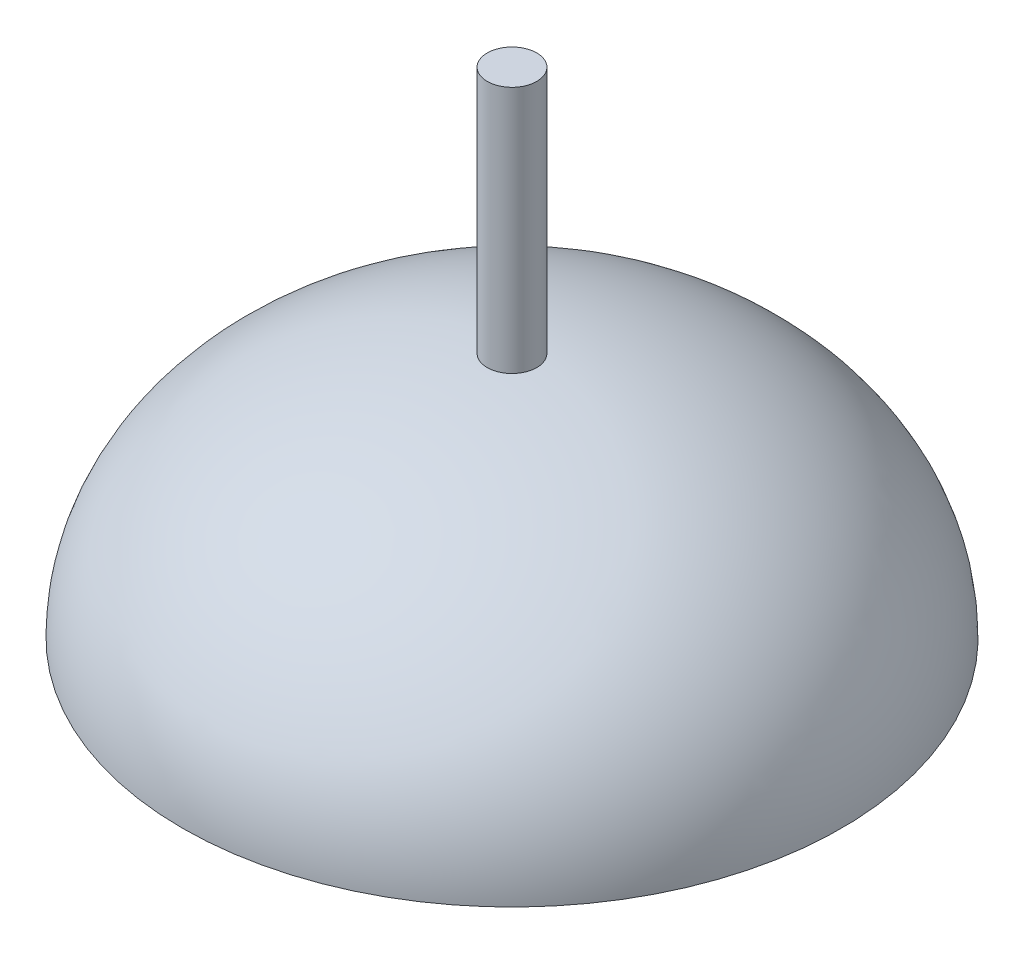
SolidWorks part; units mm, degrees
ref_plane "Piano frontale" through (0, 0, 0) normal (0, 0, 1) x (1, 0, 0)
ref_plane "Piano superiore" through (0, 0, 0) normal (0, 1, 0) x (1, 0, 0)
ref_plane "Piano destro" through (0, 0, 0) normal (1, 0, 0) x (0, 0, -1)
sketch "Schizzo1" plane through (0, 0, 0) normal (0, 0, 1) x (1, 0, 0)
  line L2 (0, 280.9975) -> (0, 300)
  line L3 (377.9261, 0) -> (400, 0)
  line L4 (0, 300) -> (0, 0) construction
  ellipse E0 centre (0, 0) end of major axis (400, 0) minor radius 300 (400, 0) -> (0, 300) ccw
  ellipse E1 centre (0, 0) end of major axis (377.9261, 0) minor radius 280.9975 (377.9261, 0) -> (0, 280.9975) ccw
  dimension "D1" = 400
  dimension "D2" = 300
revolve "Rivoluzione2" add sketch "Schizzo1" angle 360 about L4
sketch "Schizzo6" plane through (0, 0, 0) normal (0, 1, 0) x (1, 0, 0)
  circle A0 centre (0, 0) radius 30
  dimension "D1" = 60
extrude "Estrusione-Estrusione1" add sketch "Schizzo6" along normal blind 600 and the other way blind 100
sketch "Schizzo7" plane through (0, -100, 0) normal (0, -1, 0) x (1, 0, 0)
  circle A0 centre (0, 0) radius 49.1113
extrude "Estrusione-Estrusione2" add sketch "Schizzo7" along normal blind 10
